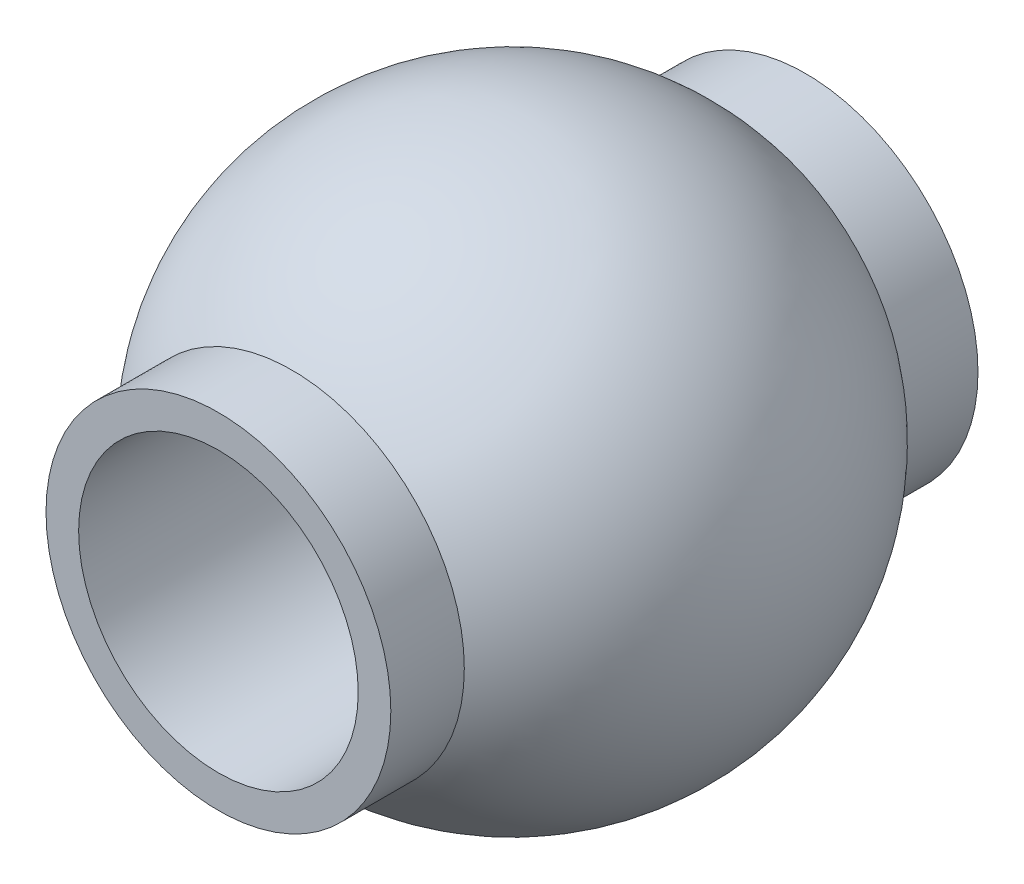
SolidWorks part; units mm, degrees
ref_plane "前视基准面" through (0, 0, 0) normal (0, 0, 1) x (1, 0, 0)
ref_plane "上视基准面" through (0, 0, 0) normal (0, 1, 0) x (1, 0, 0)
ref_plane "右视基准面" through (0, 0, 0) normal (1, 0, 0) x (0, 0, -1)
sketch "草图1" plane through (0, 0, 0) normal (0, 0, 1) x (1, 0, 0)
  line L0 (0, -3) -> (0, 3)
  arc A0 (0, -3) -> (0, 3) centre (0, 0) ccw
  dimension "D1" = 6
revolve "旋转1" add sketch "草图1" angle 360 about L0
sketch "草图2" plane through (0, 0, 0) normal (0, 0, 1) x (1, 0, 0)
  circle A0 centre (0, 0) radius 1.85
  circle A1 centre (0, 0) radius 1.5
  dimension "D1" = 3.7
  dimension "D2" = 3
extrude "凸台-拉伸1" add sketch "草图2" along normal mid plane 6.3
sketch "草图3" plane through (0, 0, 3.15) normal (0, 0, 1) x (1, 0, 0)
  circle A0 centre (0, 0) radius 1.5 construction
  circle A1 centre (0, 0) radius 1.5
extrude "切除-拉伸1" cut sketch "草图3" against normal blind 6.3
